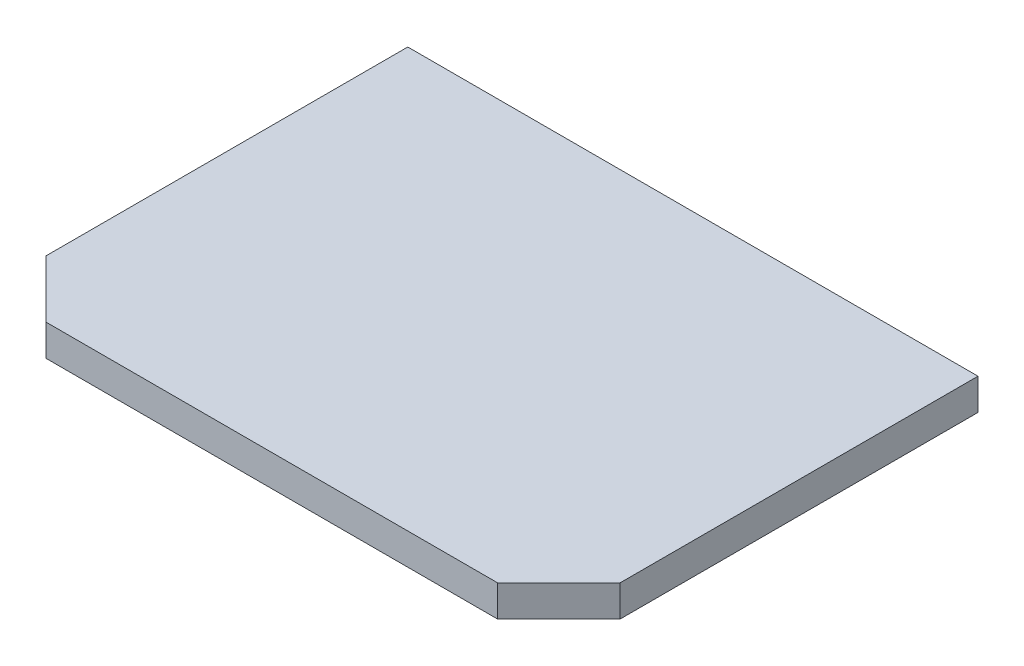
SolidWorks part; units mm, degrees
ref_plane "前视基准面" through (0, 0, 0) normal (0, 0, 1) x (1, 0, 0)
ref_plane "上视基准面" through (0, 0, 0) normal (0, 1, 0) x (1, 0, 0)
ref_plane "右视基准面" through (0, 0, 0) normal (1, 0, 0) x (0, 0, -1)
sketch "草图1" plane through (0, 0, 0) normal (0, 0, 1) x (1, 0, 0)
  line L0 (-16.2273, 3.6) -> (18.2003, 3.6) construction
  line L1 (-11.2273, 5.1) -> (-11.0273, 5.1)
  line L2 (-11.0273, 5.1) -> (-11.0273, 4)
  line L3 (11.2273, 5.1) -> (11.0273, 5.1)
  line L4 (11.0273, 5.1) -> (11.0273, 4)
  line L14 (-11.2273, 5.1) -> (-18.2273, 5.1)
  line L15 (-18.2273, 5.1) -> (-18.2273, 7.1)
  line L16 (-18.2273, 7.1) -> (18.1003, 7.1)
  line L23 (-11.1273, 3.2) -> (-16.1273, 3.2)
  line L24 (-16.1273, 3.2) -> (-16.1273, 4)
  line L29 (-18.3273, -0.1) -> (-15.3773, -0.1)
  line L30 (-15.3773, -0.1) -> (-15.3773, 2.0001)
  line L31 (-15.3773, 2.0001) -> (-11.1273, 2.0001)
  line L32 (-11.1273, 2.0001) -> (-11.1273, 3.2)
  line L33 (-11.1273, 3.2) -> (-16.1273, 3.2)
  line L47 (18.1003, 5.1) -> (18.1003, 7.1)
  line L48 (18.1003, 5.1) -> (11.2273, 5.1)
  line L57 (15.5003, -0.1) -> (18.2003, -0.1)
  line L58 (18.2003, -0.1) -> (18.2003, 5.2)
  line L63 (16.1278, 3.2) -> (11.1273, 3.2)
  line L64 (11.1273, 3.2) -> (11.1273, 1.9481)
  line L65 (11.1273, 1.9481) -> (15.5003, 1.9481)
  line L66 (15.5003, 1.9481) -> (15.5003, -0.1)
  line L73 (16.1278, 3.2) -> (-11.1273, 3.2)
  line L302 (-14.5724, 5.05) -> (14.1914, 5.05) construction
  line L307 (-11.0273, 4) -> (-16.1273, 4)
  line L308 (-16.1273, 4) -> (-16.1273, 3.2)
  line L310 (16.2281, 4.1) -> (11.2273, 4.1) construction
  line L388 (11.0273, 4) -> (16.1278, 4)
  line L389 (16.1278, 4) -> (16.1278, 3.2)
  line L420 (-16.1273, 4) -> (-11.1273, 4)
  line L421 (-16.1273, 4) -> (-11.1273, 4)
  line L422 (-11.1273, 4) -> (-11.1273, 5.2)
  line L423 (-11.1273, 5.2) -> (-18.3273, 5.2)
  line L424 (-18.3273, 5.2) -> (-18.3273, -0.1)
  line L425 (18.2003, 5.2) -> (11.1273, 5.2)
  line L426 (11.1273, 5.2) -> (11.1273, 4)
  line L427 (11.1273, 4) -> (16.1281, 4)
  line L428 (11.1273, 4) -> (16.1281, 4)
  line L429 (16.1281, 4) -> (16.1278, 3.2)
  line L430 (16.1281, 4) -> (16.1278, 3.2)
  dimension "D1" = 0.1
  dimension "D2" = 2
  dimension "D3" = 0.1
  dimension "D4" = 0.2
  dimension "D5" = 0.2
  dimension "D7" = 0.05
  dimension "D10" = 0.1
extrude "凸台-拉伸1" add sketch "草图1" along normal offset from surface 0.5 and the other way blind 12
sketch "草图2" plane through (0, 0, 5.1241) normal (0, 0, 1) x (1, 0, 0)
  line L0 (11.0273, 5.1) -> (-11.0273, 5.1)
  line L5 (16.1278, 4) -> (11.0273, 4)
  line L6 (11.0273, 4) -> (11.0273, 5.1)
  line L13 (-16.1273, 3.2) -> (16.1278, 3.2)
  line L14 (-16.1273, 4) -> (-16.1273, 3.2)
  line L17 (-11.0273, 4) -> (-16.1273, 4)
  line L18 (11.0273, 5.1) -> (18.1003, 5.1)
  line L19 (11.0273, 5.1) -> (18.1003, 5.1)
  line L20 (18.1003, 5.1) -> (18.1003, 7.1)
  line L21 (18.1003, 5.1) -> (18.1003, 7.1)
  line L22 (18.1003, 7.1) -> (-18.2273, 7.1)
  line L23 (18.1003, 7.1) -> (-18.2273, 7.1)
  line L36 (-18.2273, 7.1) -> (-18.2273, 5.1)
  line L37 (-18.2273, 7.1) -> (-18.2273, 5.1)
  line L38 (-18.2273, 5.1) -> (-11.0273, 5.1)
  line L39 (-18.2273, 5.1) -> (-11.0273, 5.1)
  line L40 (-11.0273, 5.1) -> (-11.0273, 4)
  line L42 (16.1278, 3.2) -> (16.1278, 4)
  point P4 (-2.9853, 5.1)
  point P6 (10.9351, 5.1)
  dimension "D1" = 0
extrude "凸台-拉伸2" add sketch "草图2" along normal blind 10
sketch "草图3" plane through (0, 7.1, 0) normal (0, 1, 0) x (1, 0, 0)
  line L0 (18.1003, -10.7944) -> (14.1914, -14.7033)
  line L1 (14.1914, -14.7033) -> (-14.5724, -14.7033)
  line L2 (-14.5724, -14.7033) -> (-18.2273, -11.0484)
  line L3 (18.1003, -5.1241) -> (-18.2273, -5.1241)
  line L4 (-18.2273, 12) -> (-18.2273, -15.1241)
  line L5 (-18.2273, -15.1241) -> (18.1003, -15.1241)
  line L6 (18.1003, -15.1241) -> (18.1003, 12)
  line L7 (18.1003, 12) -> (-18.2273, 12)
  line L8 (-18.2273, -5.1241) -> (-18.2273, -11.0484)
  line L10 (18.1003, -10.7944) -> (18.1003, -5.1241)
  line L12 (18.1003, -5.1241) -> (22.5409, -5.1241)
  line L13 (22.5409, -5.1241) -> (22.5409, -17.3615)
  line L14 (22.5409, -17.3615) -> (-20.378, -17.3615)
  line L15 (-20.378, -17.3615) -> (-20.378, -5.4488)
  line L16 (-20.378, -5.4488) -> (-18.2273, -5.1241)
  line M9 (-18.2273, 12) -> (-18.2273, -15.1241)
  line M10 (-18.2273, -15.1241) -> (18.1003, -15.1241)
  line M11 (18.1003, -15.1241) -> (18.1003, 12)
  dimension "D1" = 0
extrude "切除-拉伸1" cut sketch "草图3" against normal through all both and the other way through all contours L16 L15 L14 L13 L12 M11 M10 M9 | L1 L2 L0 M9 M10 M11
